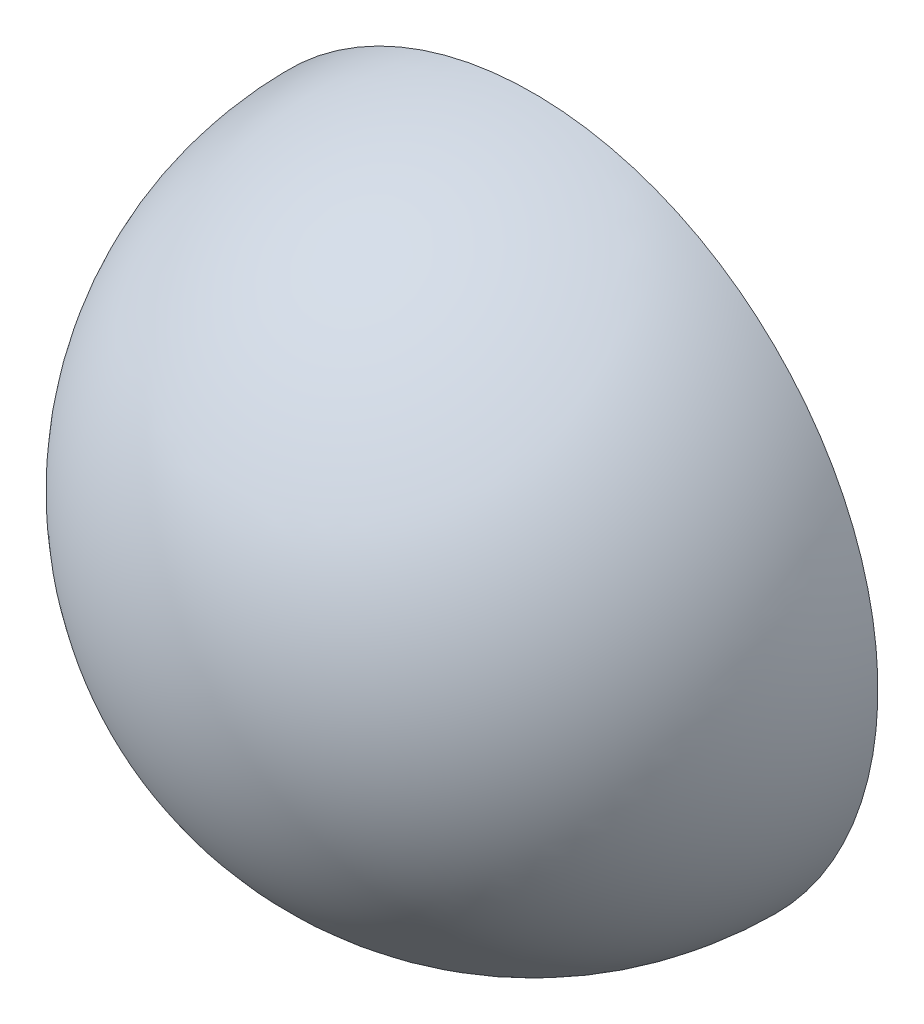
SolidWorks part; units mm, degrees
material "Настроенная пользователем пластмасса"
ref_plane "Спереди" through (0, 0, 0) normal (0, 0, 1) x (1, 0, 0)
ref_plane "Сверху" through (0, 0, 0) normal (0, 1, 0) x (1, 0, 0)
ref_plane "Справа" through (0, 0, 0) normal (1, 0, 0) x (0, 0, -1)
sketch "Эскиз1" plane through (0, 0, 0) normal (0, 1, 0) x (1, 0, 0)
  line L0 (0, 0) -> (0, -3)
  line L1 (0, 0) -> (-3, 0)
  line L2 (0, 0) -> (0, -5.1258) construction
  arc A0 (0, -3) -> (-3, 0) centre (0, 0) cw
  dimension "D1" = 6
revolve "Повернуть1" add sketch "Эскиз1" angle 360 about L2
